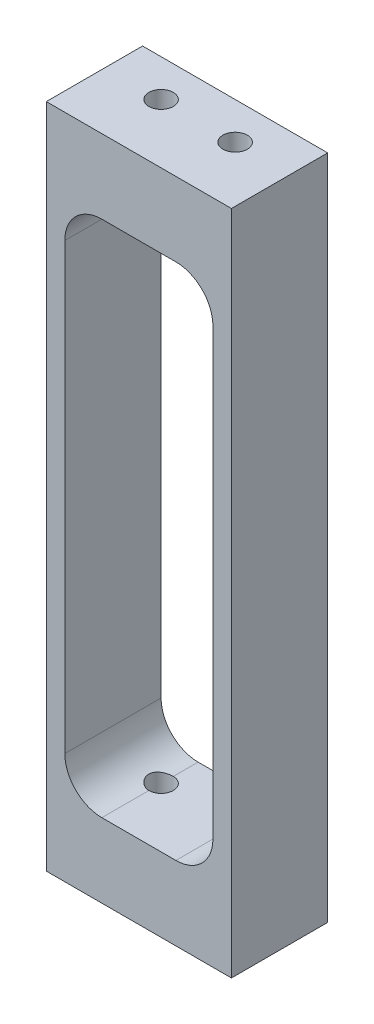
SolidWorks part; units mm, degrees
ref_plane "Front Plane" through (0, 0, 0) normal (0, 0, 1) x (1, 0, 0)
ref_plane "Top Plane" through (0, 0, 0) normal (0, 1, 0) x (1, 0, 0)
ref_plane "Right Plane" through (0, 0, 0) normal (1, 0, 0) x (0, 0, -1)
sketch "Sketch1" plane through (0, 0, 0) normal (0, 0, 1) x (1, 0, 0)
  line L1 (-12.5, -45) -> (12.5, -45)
  line L2 (-12.5, -45) -> (-12.5, 45)
  line L3 (-12.5, 45) -> (12.5, 45)
  line L4 (12.5, -45) -> (12.5, 45)
  line L5 (-12.5, -45) -> (12.5, 45) construction
  line L6 (-12.5, 45) -> (12.5, -45) construction
  point P0 (0, 0)
  dimension "D1" = 90
  dimension "D2" = 25
extrude "Boss-Extrude1" add sketch "Sketch1" along normal blind 13
sketch "Sketch2" plane through (0, 0, 13) normal (0, 0, 1) x (1, 0, 0)
  line L1 (-10, -35) -> (10, -35)
  line L2 (-10, -35) -> (-10, 35)
  line L3 (-10, 35) -> (10, 35)
  line L4 (10, -35) -> (10, 35)
  line L5 (-10, -35) -> (10, 35) construction
  line L6 (-10, 35) -> (10, -35) construction
  point P0 (0, 0)
  dimension "D1" = 20
  dimension "D2" = 70
extrude "Cut-Extrude1" cut sketch "Sketch2" against normal blind 23
fillet "Fillet1" radius 5 4 edges at (-10, 35, 6.5) (10, 35, 6.5) (10, -35, 6.5) (-10, -35, 6.5)
hole_wizard "M4x0.7 Tapped Hole1" positions "Sketch3" profile "Sketch4" tap size "M4x0.7" standard "ANSI Metric" end condition through all
sketch "Sketch3" plane through (0, -45, 0) normal (0, -1, 0) x (-1, 0, 0)
  line L0 (-5, -5) -> (5, -5)
  line L2 (12.5, -13) -> (-12.5, -13) construction
  point P1 (-5, -5)
  point P2 (5, -5)
  point P7 (0, -5)
  dimension "D1" = 10
  dimension "D2" = 8
sketch "Sketch4" plane through (5, -45, 5) normal (1, 0, 0) x (0, 0, -1)
  line L0 (0, 0) -> (0, 90)
  line L1 (0, 90) -> (1.65, 90)
  line L2 (1.65, 90) -> (1.65, 0)
  line L5 (1.65, 0) -> (0, 0)
  line L11 (0, -6.35) -> (0, 107.95) construction
  dimension "Thru Tap Drill Dia." = 3.3
  dimension "Thru Tap Drill Depth" = 90
cosmetic thread "Hole Thread1" parameters "D2"=4
cosmetic thread "Hole Thread2" parameters "D2"=4
